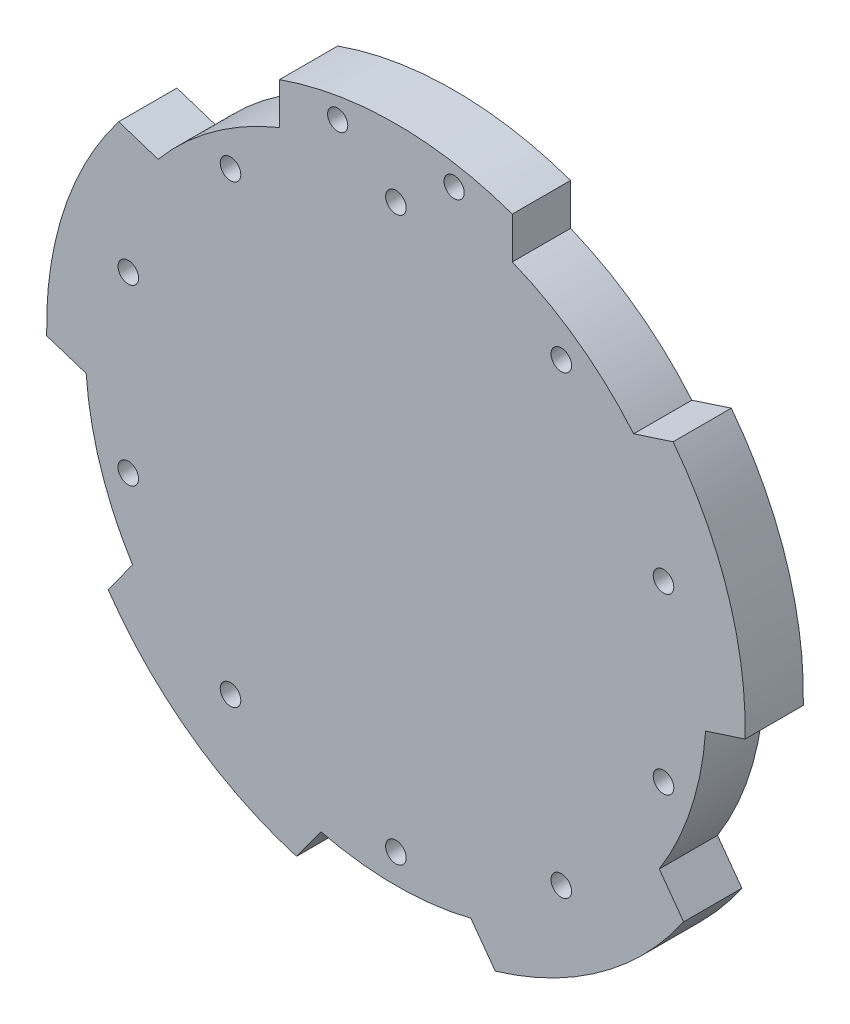
SolidWorks part; units mm, degrees
ref_plane "Ebene vorne" through (0, 0, 0) normal (0, 0, 1) x (1, 0, 0)
ref_plane "Ebene oben" through (0, 0, 0) normal (0, 1, 0) x (1, 0, 0)
ref_plane "Ebene rechts" through (0, 0, 0) normal (1, 0, 0) x (0, 0, -1)
sketch "Skizze1" plane through (0, 0, 0) normal (0, 0, 1) x (1, 0, 0)
  circle A0 centre (0, 0) radius 80
  dimension "D1" = 160
extrude "Aufsatz-Linear austragen1" add sketch "Skizze1" along normal blind 15
ref_plane "Ebene1" through (0, 0, 0) normal (0, 1, 0) x (1, 0, 0)
sketch "Skizze2" plane through (0, 0, 0) normal (0, 1, 0) x (1, 0, 0)
  line L0 (-62.75, -15) -> (-57.25, -15)
  line L1 (-80, -15) -> (80, -15) construction
  line L3 (0, 0) -> (0, -1000) construction
  arc A0 (-62.75, -15) -> (-57.25, -15) centre (-60, -15.75) cw
  dimension "D1" = 5.5
  dimension "D2" = 0
  dimension "D3" = 0
  dimension "D4" = 0.75
  dimension "D5" = 60
sketch "Skizze8" plane through (0, 0, 0) normal (0, 0, -1) x (-1, 0, 0)
  circle A0 centre (0, -72.5) radius 2.65
  dimension "D2" = 5.3
  dimension "D1" = 72.5
extrude "Schnitt-Linear austragen1" cut sketch "Skizze8" against normal blind 15
pattern_circular "Kreismuster1" count 10 over 360 about axis through (0, 0, 0) along (0, 0, 1) of "Schnitt-Linear austragen1"
sketch "Skizze9" plane through (0, 0, 0) normal (0, 0, -1) x (-1, 0, 0)
  circle A0 centre (0, -72.5) radius 4.5
  dimension "D1" = 9
extrude "Schnitt-Linear austragen2" cut sketch "Skizze9" against normal blind 5
pattern_circular "Kreismuster2" count 10 over 360 about axis through (0, 0, 0) along (0, 0, 1) of "Schnitt-Linear austragen2"
ref_plane "Ebene2" through (0, 80, 0) normal (0, 1, 0) x (1, 0, 0)
sketch "Skizze10" plane through (0, 0, 15) normal (0, 0, 1) x (1, 0, 0)
  line L0 (55, 80) -> (-55, 80) construction
  line L2 (-30, 69.8528) -> (-30, 84.8528)
  line L4 (30, 69.8528) -> (30, 84.8528)
  line L5 (-30, 69.8528) -> (21.7085, 87.3427) construction
  line L6 (-21.7085, 87.3427) -> (30, 69.8528) construction
  line L7 (-30, 69.8528) -> (0, 80)
  line L8 (0, 80) -> (30, 69.8528)
  arc A0 (30, 84.8528) -> (-30, 84.8528) centre (0, 0) ccw
  point P3 (0, 80)
  dimension "D1" = 30
  dimension "D6" = 90
  dimension "D2" = 30
  dimension "D3" = 80
  dimension "D4" = 15
  dimension "D5" = 15
extrude "Aufsatz-Linear austragen2" add sketch "Skizze10" against normal blind 15
pattern_circular "Kreismuster3" count 5 over 360 about axis through (0, 0, 0) along (0, 0, 1) of "Aufsatz-Linear austragen2"
sketch "Skizze11" plane through (0, 0, 15) normal (0, 0, 1) x (1, 0, 0)
  circle A0 centre (-15, 83.4) radius 2.6
  circle A1 centre (15, 83.4) radius 2.6
  circle A2 centre (0, 72.5) radius 2.65 construction
  dimension "D3" = 5.2
  dimension "D4" = 5.2
  dimension "D5" = 83.4
  dimension "D1" = 15
  dimension "D2" = 15
  dimension "D6" = 83.4
extrude "Schnitt-Linear austragen3" cut sketch "Skizze11" against normal blind 15
sketch "Skizze12" plane through (0, 0, 15) normal (0, 0, 1) x (1, 0, 0)
  circle A0 centre (0, 0) radius 80
  circle A1 centre (-15, 83.4) radius 4.5
  circle A2 centre (15, 83.4) radius 4.5
